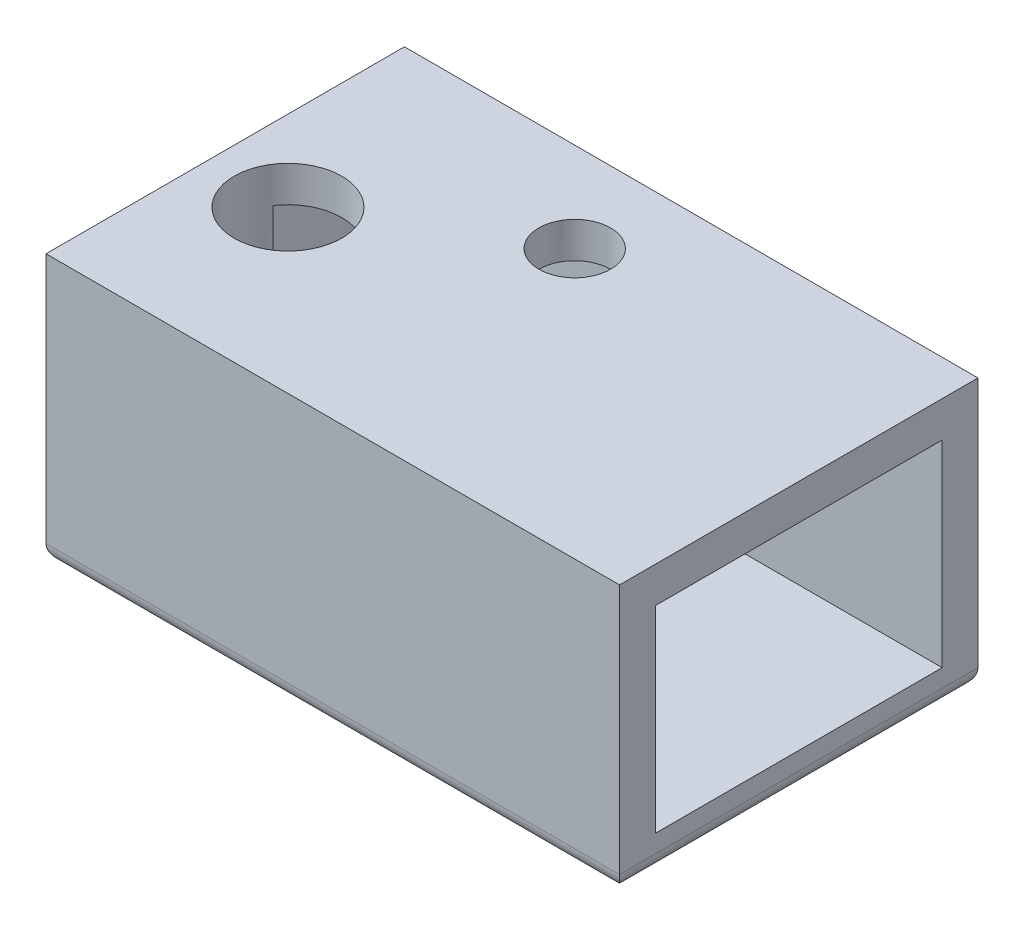
SolidWorks part; units mm, degrees
ref_plane "Front Plane" through (0, 0, 0) normal (0, 0, 1) x (1, 0, 0)
ref_plane "Top Plane" through (0, 0, 0) normal (0, 1, 0) x (1, 0, 0)
ref_plane "Right Plane" through (0, 0, 0) normal (1, 0, 0) x (0, 0, -1)
sketch "Sketch1" plane through (0, 0, 0) normal (0, 1, 0) x (1, 0, 0)
  line L1 (-15, -8) -> (15, -8)
  line L2 (-15, -8) -> (-15, 8)
  line L3 (-15, 8) -> (15, 8)
  line L4 (15, -8) -> (15, 8)
  line L5 (-15, -8) -> (15, 8) construction
  line L6 (-15, 8) -> (15, -8) construction
  point P0 (0, 0)
  dimension "D1" = 30
  dimension "D2" = 16
extrude "Boss-Extrude1" add sketch "Sketch1" along normal blind 11
shell "Shell1" thickness 2
sketch "Sketch4" plane through (0, 13, 0) normal (0, 1, 0) x (1, 0, 0)
  line L1 (-15, 8) -> (-15, -8) construction
  line L2 (-17, 0) -> (15, 0) construction
  line L3 (-17, 10) -> (-17, -10) construction
  line L4 (15, -10) -> (15, 10) construction
  circle A0 centre (-12.5, -1) radius 3
  circle A1 centre (-2.5, 5) radius 2
  dimension "D1" = 6
  dimension "D2" = 2.5
  dimension "D3" = 1
  dimension "D4" = 10
  dimension "D5" = 6
  dimension "D6" = 4
extrude "Cut-Extrude3" cut sketch "Sketch4" against normal up to surface (13 mm away) up to face at (0, 0, 0)
fillet "Fillet1" radius 1 4 edges at (-17, -2, 0) (-1, -2, -10) (15, -2, 0) (-1, -2, 10)
